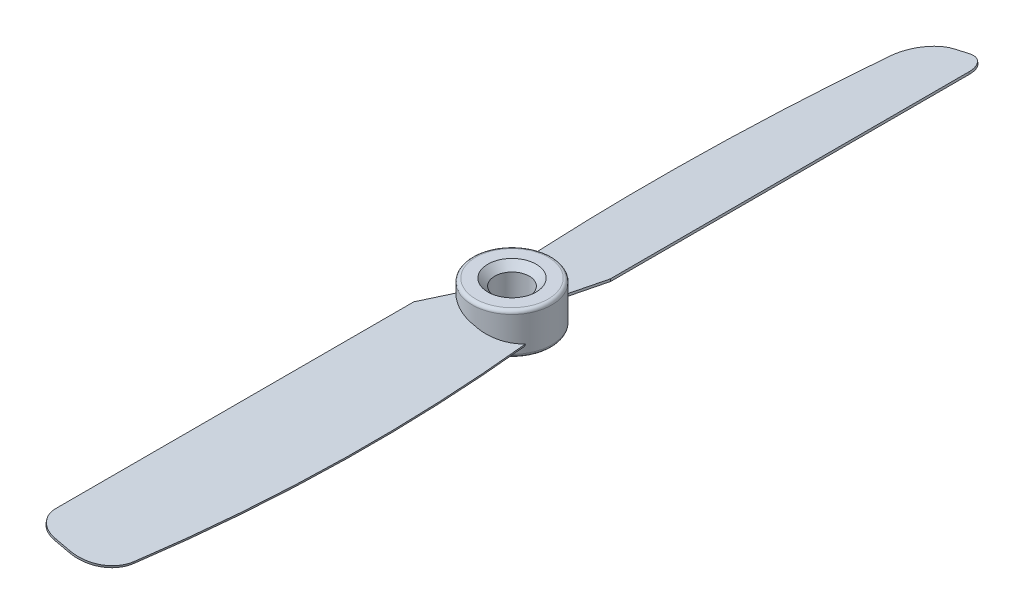
SolidWorks part; units mm, degrees
ref_plane "Front Plane" through (0, 0, 0) normal (0, 0, 1) x (1, 0, 0)
ref_plane "Top Plane" through (0, 0, 0) normal (0, 1, 0) x (1, 0, 0)
ref_plane "Right Plane" through (0, 0, 0) normal (1, 0, 0) x (0, 0, -1)
sketch "Sketch1" plane through (0, 0, 0) normal (0, 1, 0) x (1, 0, 0)
  circle A0 centre (0, 0) radius 5.75
  dimension "D1" = 11.5
extrude "Boss-Extrude1" add sketch "Sketch1" along normal mid plane 6
sketch "Sketch2" plane through (0, 0, 0) normal (0, 0, 1) x (1, 0, 0)
  line L0 (-5.75, 1.3275) -> (5.75, -1.3275) construction
  line L1 (-5.75, 3) -> (-5.75, -3) construction
  line L2 (5.75, -3) -> (5.75, 3) construction
  line L3 (-5.75, -3) -> (5.75, -3) construction
  dimension "D1" = 13
ref_plane "Plane1" through (0, 0, 0) normal (-0.225, -0.9744, 0) x (0.9744, -0.225, 0)
sketch "Sketch3" plane through (0, 0, 0) normal (-0.225, -0.9744, 0) x (0.9744, -0.225, 0)
  line L0 (-3.9461, 3.2513) -> (-5.8592, 8.5486)
  line L1 (-5.8592, 8.5486) -> (-5.8592, 60.5)
  line L2 (-2.8592, 63.5) -> (-0.5504, 63.5)
  arc A0 (4.4142, 59.0935) -> (-0.5504, 63.5) centre (-0.5504, 58.5) ccw
  arc A1 (-5.8592, 60.5) -> (-2.8592, 63.5) centre (-2.8592, 60.5) cw
  ellipse E0 centre (0.6749, 0) end of major axis (0.6749, 5.75) minor radius 5.6026 construction
  ellipse E1 centre (0.6749, 0) end of major axis (0.6749, 5.75) minor radius 5.6026 (5.2958, 3.2513) -> (-3.9461, 3.2513) ccw
  spline S0 degree 3 poles (5.2958, 3.2513) (6.9284, 21.8916) (6.6342, 40.5221) (4.4142, 59.0935) knots 0 0 0 0 0.926693 0.926693 0.926693 0.926693
  dimension "D2" = 5
  dimension "D3" = 3
  dimension "D1" = 63.5
extrude "Boss-Extrude2" add sketch "Sketch3" along normal mid plane 0.3
pattern_circular "CirPattern1" count 2 over 360 about axis through (0, 3, 0) along (0, 1, 0) of "Boss-Extrude2"
sketch "Sketch4" plane through (0, 3, 0) normal (0, 1, 0) x (1, 0, 0)
  circle A0 centre (0, 0) radius 2.5
  dimension "D1" = 5
extrude "Cut-Extrude1" cut sketch "Sketch4" against normal through all
fillet "Fillet1" radius 0.5 2 edges at (0, 3, 5.75) (0, -3, 5.75)
chamfer "Chamfer1" distance 1 angle 45 2 edges at (0, 3, 2.5) (0, -3, 2.5)
